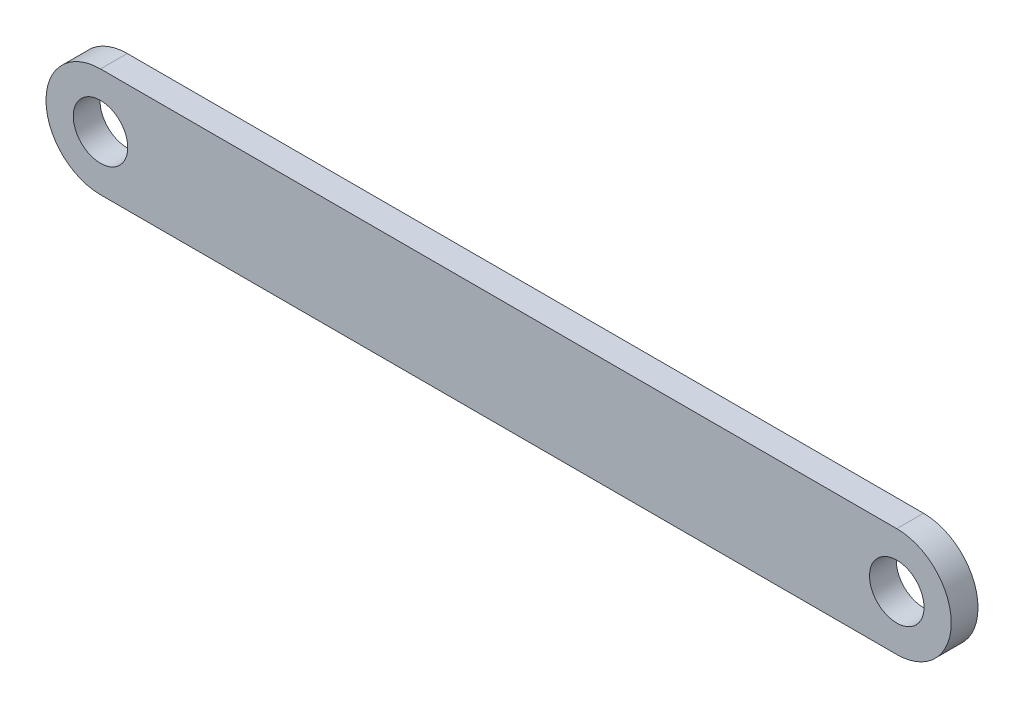
SolidWorks part; units mm, degrees
ref_plane "Спереди" through (0, 0, 0) normal (0, 0, 1) x (1, 0, 0)
ref_plane "Сверху" through (0, 0, 0) normal (0, 1, 0) x (1, 0, 0)
ref_plane "Справа" through (0, 0, 0) normal (1, 0, 0) x (0, 0, -1)
sketch "Sketch1" plane through (0, 0, 0) normal (0, 0, 1) x (1, 0, 0)
  line L0 (0, 0) -> (-29.7762, 0)
  line L1 (-29.7762, 2.038) -> (0, 2.038)
  line L2 (-29.7762, -2.038) -> (0, -2.038)
  circle A0 centre (0, 0) radius 1.019
  circle A1 centre (0, 0) radius 2.038
  circle A2 centre (-29.7762, 0) radius 1.019
  circle A3 centre (-29.7762, 0) radius 2.038
  dimension "D1" = 29.7762
extrude "Extrude1" add sketch "Sketch1" along normal blind 1
